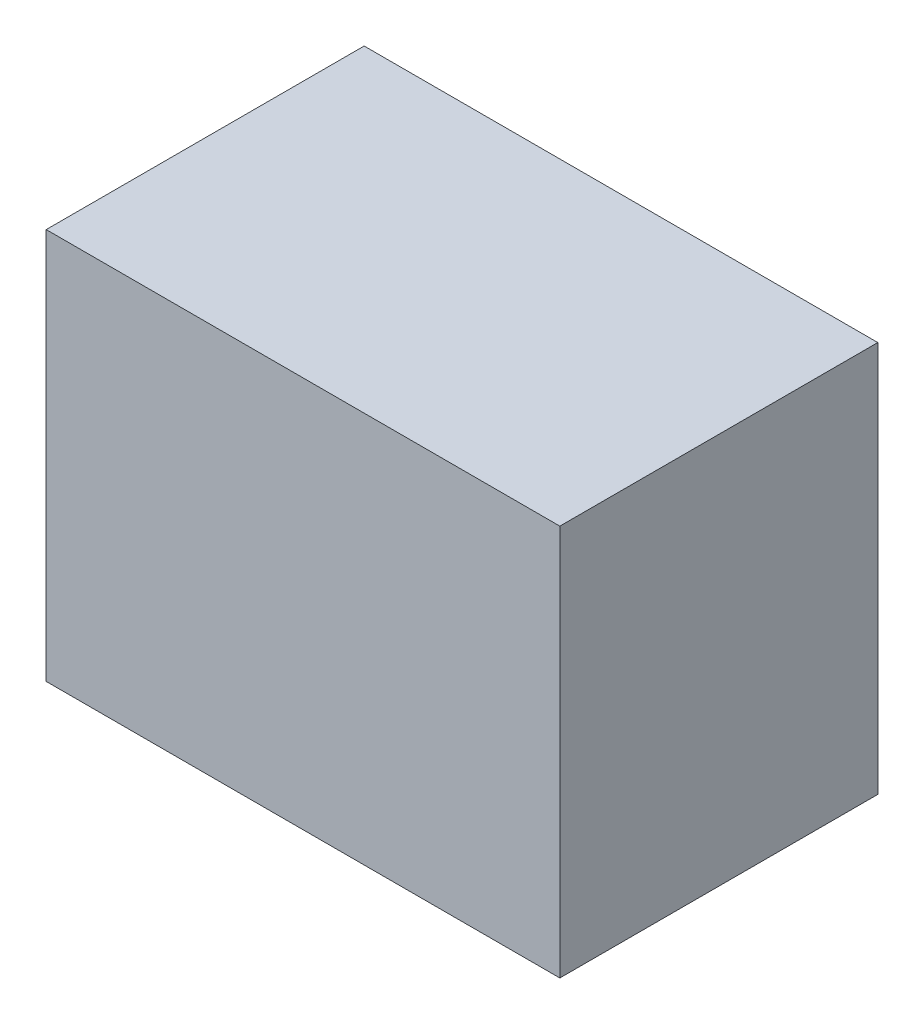
SolidWorks part; units mm, degrees
material "PET"
ref_plane "Front Plane" through (0, 0, 0) normal (0, 0, 1) x (1, 0, 0)
ref_plane "Top Plane" through (0, 0, 0) normal (0, 1, 0) x (1, 0, 0)
ref_plane "Right Plane" through (0, 0, 0) normal (1, 0, 0) x (0, 0, -1)
sketch "Sketch1" plane through (0, 0, 0) normal (0, 0, 1) x (1, 0, 0)
  line L0 (-10, 10) -> (410, 10)
  line L1 (0, 0) -> (400, 0)
  line L2 (0, 0) -> (0, -300)
  line L3 (0, -300) -> (400, -300)
  line L4 (400, 0) -> (400, -300)
  line L5 (410, 10) -> (410, -310)
  line L6 (-10, -310) -> (410, -310)
  line L7 (-10, 10) -> (-10, -310)
  dimension "D1" = 400
  dimension "D2" = 300
  dimension "D3" = 10
extrude "Boss-Extrude1" add sketch "Sketch1" along normal blind 250
sketch "Sketch2" plane through (0, 0, 250) normal (0, 0, 1) x (1, 0, 0)
  line L5 (-10, 10) -> (410, 10)
  line L6 (-10, 10) -> (-10, -310)
  line L7 (-10, -310) -> (410, -310)
  line L8 (410, 10) -> (410, -310)
extrude "Boss-Extrude2" add sketch "Sketch2" along normal blind 10
